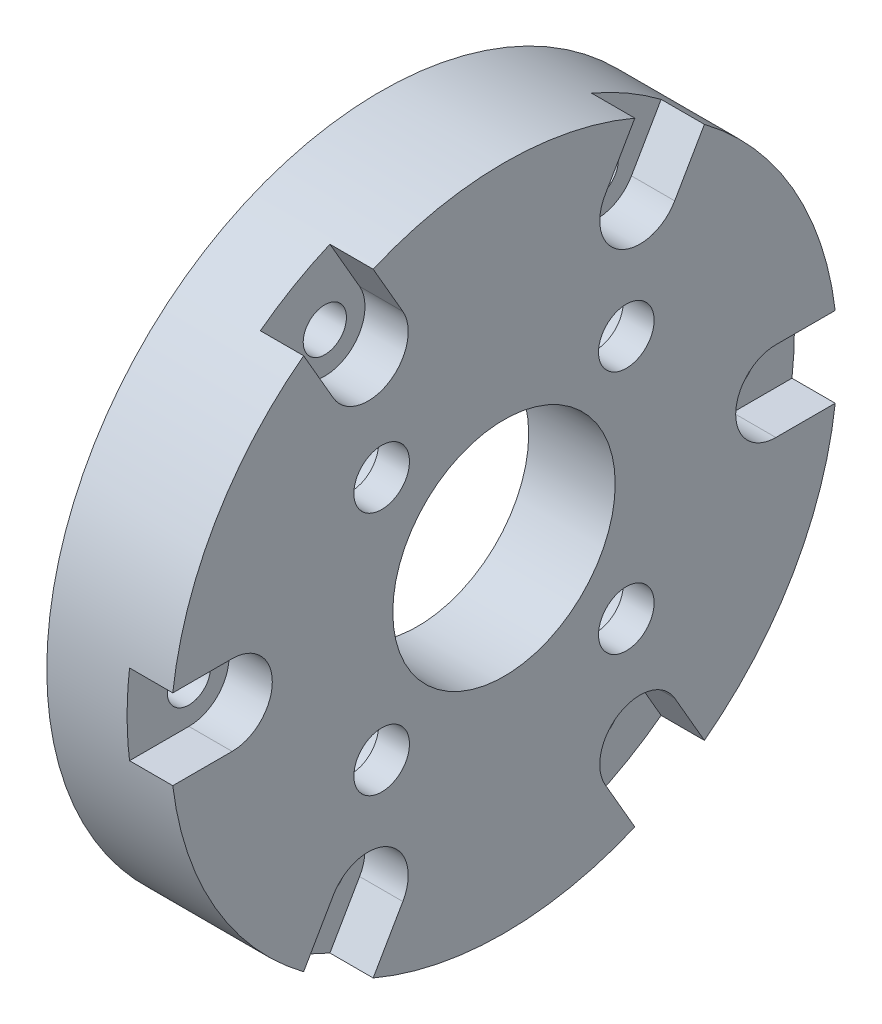
SolidWorks part; units mm, degrees
ref_plane "Plan1" through (0, 0, 0) normal (0, 0, 1) x (1, 0, 0)
ref_plane "Plan2" through (0, 0, 0) normal (0, 1, 0) x (1, 0, 0)
ref_plane "Plan3" through (0, 0, 0) normal (1, 0, 0) x (0, 0, -1)
sketch "Esquisse1" plane through (0, 0, 0) normal (0, 0, 1) x (1, 0, 0)
  line L0 (-5, 27) -> (-5, 19)
  line L1 (-5, 19) -> (-2, 19)
  line L2 (-2, 19) -> (-2, 9)
  line L3 (-2, 9) -> (5, 9)
  line L4 (5, 9) -> (5, 27)
  line L5 (5, 27) -> (-5, 27)
  line L8 (5, 17.9) -> (5, 9) construction
  line L9 (5, 9) -> (2, 9) construction
  line L10 (-3, 19) -> (-3, 8) construction
  line L12 (-5, 25) -> (-5, 19) construction
  line L13 (92.6, 0) -> (-33.4, 0) construction
  line L15 (-14.9364, 0) -> (44.8605, 0) construction
  dimension "D1" = 1
  dimension "D2" = 18
  dimension "D3" = 10
  dimension "D4" = 8
  dimension "D5" = 10
revolve "Base-Révolution" add sketch "Esquisse1" angle 360 about L15
sketch "Esquisse2" plane through (5, 0, 0) normal (1, 0, 0) x (0, 0, -1)
  line L0 (0, 0) -> (-24.5, 0) construction
  line L1 (-22, 3.25) -> (-28.5433, 3.25)
  line L2 (-22, -3.25) -> (-28.5433, -3.25)
  line L3 (-28.5433, -3.25) -> (-28.5433, 3.25)
  circle A0 centre (0, 0) radius 22 construction
  arc A2 (-22, -3.25) -> (-22, 3.25) centre (-22, 0) ccw
  dimension "D1" = 44
  dimension "D2" = 6.5
extrude "Enlèv. mat.-Extru.1" cut sketch "Esquisse2" against normal blind 3.5
pattern_circular "Répétition circulaire1" count 6 over 360 about axis through (0, 0, 0) along (1, 0, 0) of "Enlèv. mat.-Extru.1"
sketch "Esquisse3" plane through (1.5, 0, 0) normal (1, 0, 0) x (0, 0, -1)
  circle A0 centre (-22, 0) radius 1.75
  dimension "D1" = 3.5
extrude "Enlèv. mat.-Extru.2" cut sketch "Esquisse3" against normal through all
pattern_circular "Répétition circulaire2" count 6 over 360 about axis through (0, 0, 0) along (1, 0, 0) of "Enlèv. mat.-Extru.2"
sketch "Esquisse4" plane through (-2, 0, 0) normal (-1, 0, 0) x (0, 0, 1)
  point P0 (9.8995, 9.8995)
hole_wizard "Chambrage pour vis à tête cylindrique à 6 pans creux (vis CHC) M41" positions "Esquisse6" profile "Esquisse5" counterbore size "M4" standard "ISO" end condition through all
sketch "Esquisse6" plane through (-2, 0, 0) normal (-1, 0, 0) x (0, 0, 1)
  point P0 (9.8995, 9.8995)
sketch "Esquisse5" plane through (-2, 9.8995, 9.8995) normal (0, 1, 0) x (0, 0, 1)
  line L0 (0, 0) -> (0, 7)
  line L1 (0, 7) -> (2.25, 7)
  line L3 (2.25, 7) -> (2.25, 4.5)
  line L4 (2.25, 4.5) -> (4, 4.5)
  line L5 (4, 4.5) -> (4, 0)
  line L7 (4, 0) -> (0, 0)
  line L11 (0, -6.35) -> (0, 107.95) construction
  dimension "Diamètre du perçage jusqu'au prochain" = 4.5
  dimension "Profondeur du perçage jusqu'au prochain" = 7
  dimension "Diamètre du chambrage" = 8
  dimension "Profondeur du chambrage" = 4.5
pattern_circular "Répétition circulaire3" count 4 over 360 about axis through (0, 0, 0) along (1, 0, 0) of "Chambrage pour vis à tête cylindrique à 6 pans creux (vis CHC) M41"
